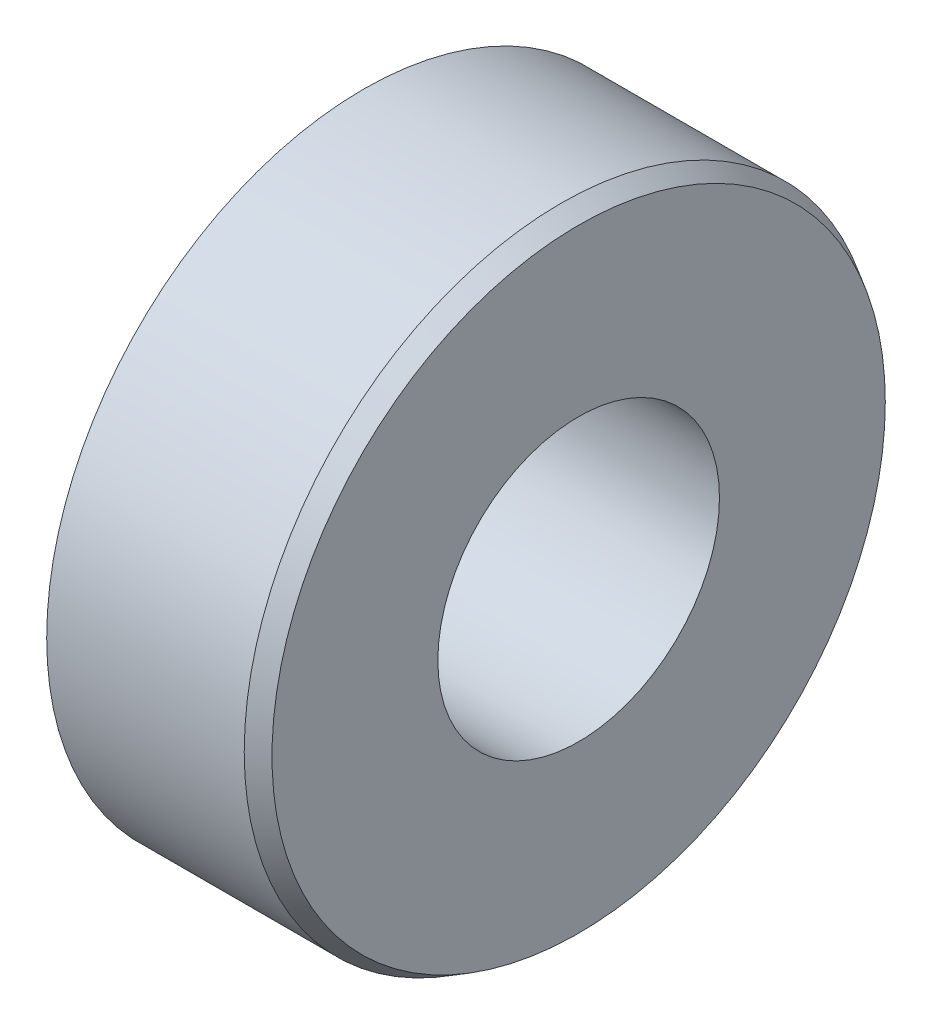
SolidWorks part; units mm, degrees
ref_plane "Piano frontale" through (0, 0, 0) normal (0, 0, 1) x (1, 0, 0)
ref_plane "Piano superiore" through (0, 0, 0) normal (0, 1, 0) x (1, 0, 0)
ref_plane "Piano destro" through (0, 0, 0) normal (1, 0, 0) x (0, 0, -1)
sketch "Schizzo1" plane through (0, 0, 0) normal (1, 0, 0) x (0, 0, -1)
  circle A0 centre (0, 0) radius 45
  circle A1 centre (0, 0) radius 20
extrude "Estrusione1" add sketch "Schizzo1" along normal blind 32
chamfer "Smusso1" distance 2.5 angle 30 2 edges at (0, 0, -45) (32, 0, -45)
ref_plane "Piano1" through (16, 0, 0) normal (1, 0, 0) x (0, 0, -1)
